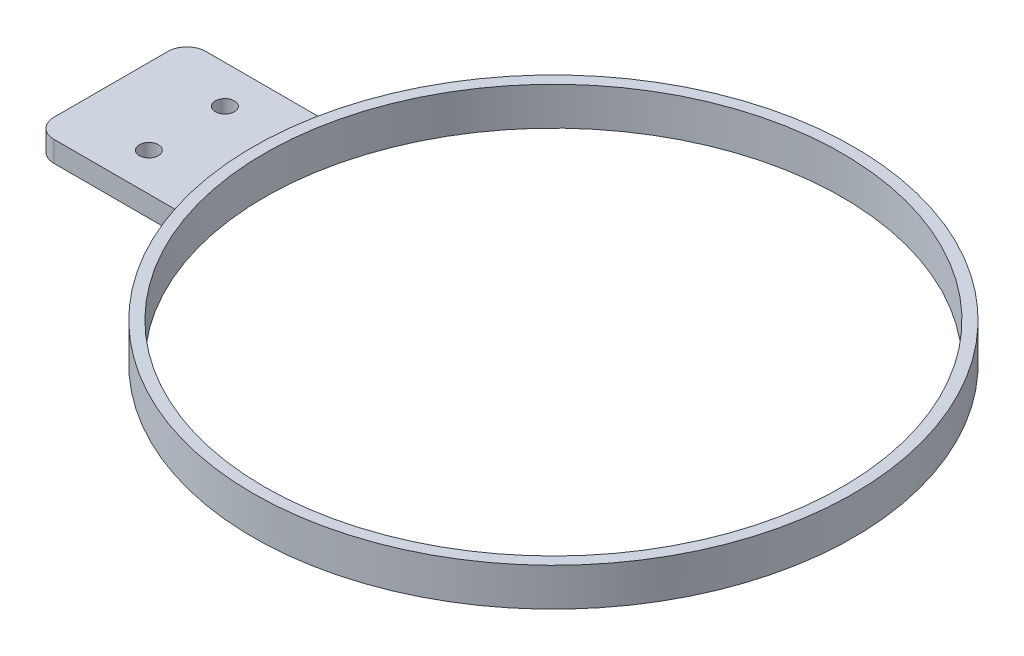
SolidWorks part; units mm, degrees
ref_plane "Alzado" through (0, 0, 0) normal (0, 0, 1) x (1, 0, 0)
ref_plane "Planta" through (0, 0, 0) normal (0, 1, 0) x (1, 0, 0)
ref_plane "Vista lateral" through (0, 0, 0) normal (1, 0, 0) x (0, 0, -1)
sketch "Croquis1" plane through (0, 0, 0) normal (0, 1, 0) x (1, 0, 0)
  line L0 (-53.7401, 53.7401) -> (-53.7401, -49.4975) construction
  line L1 (-53.7401, -49.4975) -> (-53.6415, -49.6541) construction
  line L2 (-53.7401, 53.7401) -> (53.7401, 53.7401) construction
  line L3 (53.7401, 53.7401) -> (53.7401, -51.6188) construction
  line L4 (-53.6415, -49.6541) -> (53.7401, -51.6188) construction
  line L5 (-53.7401, 53.7401) -> (53.7401, -51.6188) construction
  line L6 (-53.6415, -49.6541) -> (53.7401, 53.7401) construction
  line L7 (-76, 0) -> (76, 0) construction
  circle A0 centre (0, 0) radius 76
  circle A1 centre (0, 0) radius 79
  point P10 (0, 0)
  point P13 (0, 0)
  dimension "D1" = 152
  dimension "D2" = 3
extrude "Saliente-Extruir1" add sketch "Croquis1" along normal blind 10
sketch "Croquis2" plane through (0, 0, 0) normal (0, 1, 0) x (1, 0, 0)
  line L1 (-76.4264, 20) -> (-111.4264, 20)
  line L2 (-116.4264, 15) -> (-116.4264, -15)
  line L3 (-111.4264, -20) -> (-76.4264, -20)
  circle A0 centre (0, 0) radius 79 construction
  arc A1 (-76.4264, 20) -> (-76.4264, -20) centre (0, 0) ccw
  circle A2 centre (-96.4264, 10) radius 2.4999
  circle A3 centre (-96.4264, -10) radius 2.5
  arc A4 (-111.4264, 20) -> (-116.4264, 15) centre (-111.4264, 15) ccw
  arc A5 (-116.4264, -15) -> (-111.4264, -20) centre (-111.4264, -15) ccw
  point P14 (-116.4264, 20)
  point P17 (-116.4264, -20)
  dimension "D4" = 10
  dimension "D8" = 5
  dimension "D9" = 5
  dimension "D1" = 40
  dimension "D2" = 40
  dimension "D3" = 40
  dimension "D5" = 20
  dimension "D6" = 10
  dimension "D7" = 20
extrude "Saliente-Extruir2" add sketch "Croquis2" along normal blind 5.5
